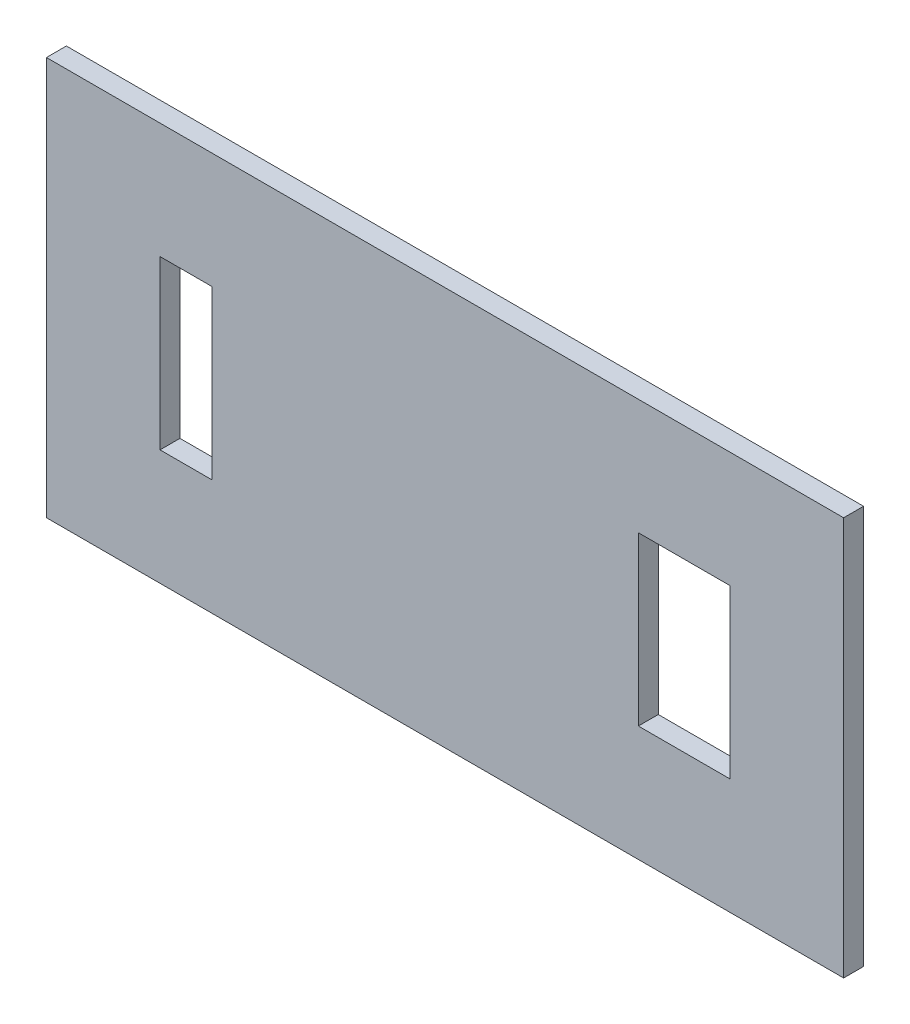
SolidWorks part; units mm, degrees
ref_plane "Front Plane" through (0, 0, 0) normal (0, 0, 1) x (1, 0, 0)
ref_plane "Top Plane" through (0, 0, 0) normal (0, 1, 0) x (1, 0, 0)
ref_plane "Right Plane" through (0, 0, 0) normal (1, 0, 0) x (0, 0, -1)
sketch "Sketch1" plane through (0, 0, 0) normal (0, 0, 1) x (1, 0, 0)
  line L1 (-25.4, 12.7) -> (25.4, 12.7)
  line L2 (-25.4, 12.7) -> (-25.4, -12.7)
  line L3 (-25.4, -12.7) -> (25.4, -12.7)
  line L4 (25.4, 12.7) -> (25.4, -12.7)
  line L5 (-25.4, 12.7) -> (25.4, -12.7) construction
  line L6 (-25.4, -12.7) -> (25.4, 12.7) construction
  line L7 (12.319, 5.334) -> (18.161, 5.334)
  line L8 (12.319, 5.334) -> (12.319, -5.334)
  line L9 (12.319, -5.334) -> (18.161, -5.334)
  line L10 (18.161, 5.334) -> (18.161, -5.334)
  line L11 (12.319, 5.334) -> (18.161, -5.334) construction
  line L12 (12.319, -5.334) -> (18.161, 5.334) construction
  line L13 (-14.859, 5.334) -> (-18.161, 5.334)
  line L14 (-14.859, 5.334) -> (-14.859, -5.334)
  line L15 (-14.859, -5.334) -> (-18.161, -5.334)
  line L16 (-18.161, 5.334) -> (-18.161, -5.334)
  line L17 (-14.859, 5.334) -> (-18.161, -5.334) construction
  line L18 (-14.859, -5.334) -> (-18.161, 5.334) construction
  point P0 (0, 0)
  point P6 (15.24, 0)
  point P11 (-16.51, 0)
  dimension "D1" = 10.668
  dimension "D2" = 3.302
  dimension "D3" = 5.842
  dimension "D4" = 16.51
  dimension "D5" = 15.24
  dimension "D6" = 50.8
  dimension "D7" = 25.4
extrude "Boss-Extrude1" add sketch "Sketch1" along normal blind 1.27
